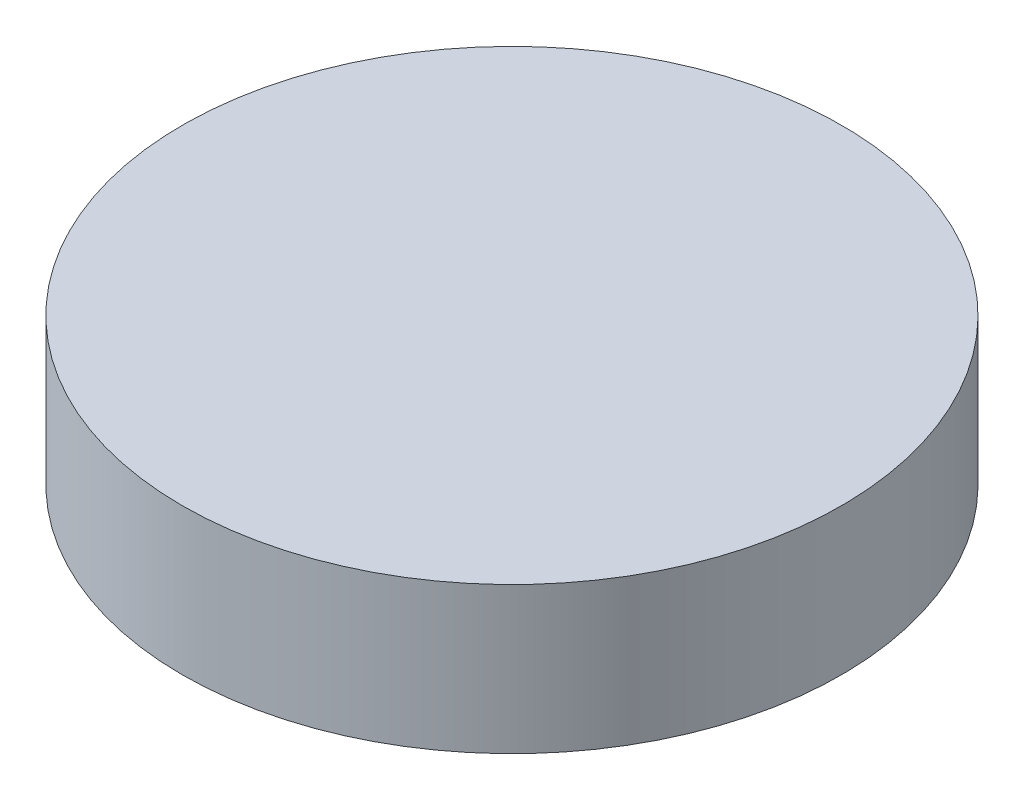
SolidWorks part; units mm, degrees
ref_plane "Front Plane" through (0, 0, 0) normal (0, 0, 1) x (1, 0, 0)
ref_plane "Top Plane" through (0, 0, 0) normal (0, 1, 0) x (1, 0, 0)
ref_plane "Right Plane" through (0, 0, 0) normal (1, 0, 0) x (0, 0, -1)
sketch "Sketch1" plane through (0, 0, 0) normal (0, 1, 0) x (1, 0, 0)
  circle A0 centre (0, 0) radius 900
  dimension "D1" = 1800
sketch "Sketch2" plane through (0, 0, 0) normal (0, 1, 0) x (1, 0, 0)
  circle A0 centre (0, 0) radius 900
extrude "Boss-Extrude1" add sketch "Sketch2" along normal blind 400
sketch "Sketch3" plane through (0, 0, 0) normal (0, -1, 0) x (-1, 0, 0)
  circle A0 centre (0, 0) radius 250
  dimension "D1" = 500
sketch "Sketch4" plane through (0, 0, 0) normal (0, -1, 0) x (-1, 0, 0)
  circle A0 centre (0, 0) radius 250
extrude "Boss-Extrude2" add sketch "Sketch4" along normal blind 50
sketch "Sketch5" plane through (0, -50, 0) normal (0, -1, 0) x (-1, 0, 0)
  circle A0 centre (0, 0) radius 200
  dimension "D1" = 400
sketch "Sketch6" plane through (0, -50, 0) normal (0, -1, 0) x (-1, 0, 0)
  circle A0 centre (0, 0) radius 200
extrude "Boss-Extrude3" add sketch "Sketch6" along normal blind 400
